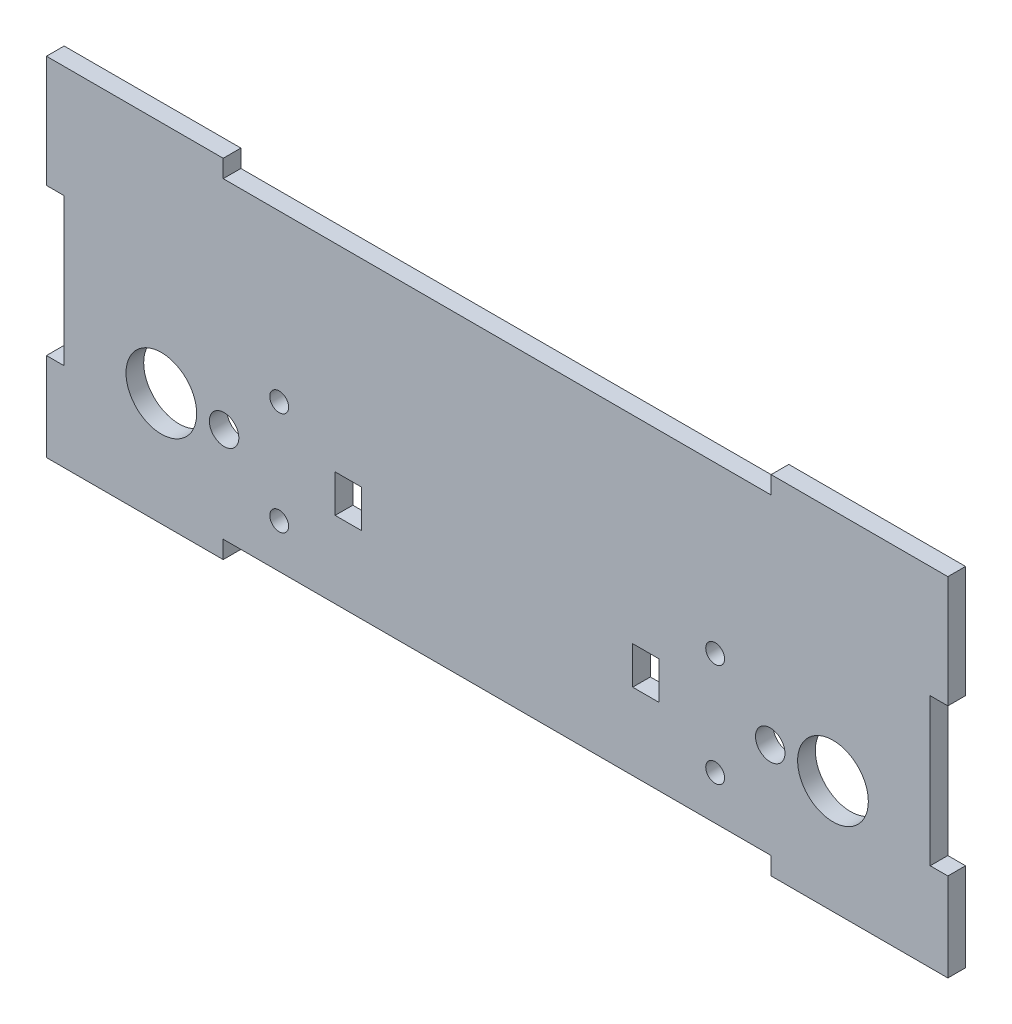
SolidWorks part; units mm, degrees
ref_plane "Plano frontal" through (0, 0, 0) normal (0, 0, 1) x (1, 0, 0)
ref_plane "Plano superior" through (0, 0, 0) normal (0, 1, 0) x (1, 0, 0)
ref_plane "Plano direito" through (0, 0, 0) normal (1, 0, 0) x (0, 0, -1)
sketch "Esboço1" plane through (0, 0, 0) normal (0, 0, 1) x (1, 0, 0)
  line L1 (-76.5, -29.5) -> (76.5, -29.5)
  line L2 (-76.5, -29.5) -> (-76.5, 29.5)
  line L3 (-76.5, 29.5) -> (76.5, 29.5)
  line L4 (76.5, -29.5) -> (76.5, 29.5)
  line L5 (-76.5, -29.5) -> (76.5, 29.5) construction
  line L6 (-76.5, 29.5) -> (76.5, -29.5) construction
  point P0 (0, 0)
  dimension "D1" = 153
  dimension "D2" = 59
extrude "Ressalto-extrusão1" add sketch "Esboço1" along normal blind 3
sketch "Esboço2" plane through (0, 0, 3) normal (0, 0, 1) x (1, 0, 0)
  line L0 (76.5, -29.5) -> (76.5, 29.5) construction
  line L1 (-76.5, 29.5) -> (76.5, 29.5)
  line L2 (-76.5, 29.5) -> (-76.5, 26.5)
  line L3 (-76.5, 26.5) -> (76.5, 26.5)
  line L4 (76.5, 29.5) -> (76.5, 26.5)
  line L5 (-46.5, 29.5) -> (-46.5, 26.5)
  line L6 (46.5, 29.5) -> (46.5, 26.5)
  line L7 (-75.0639, 0) -> (95.5788, 0) construction
  line L8 (46.5, -29.5) -> (46.5, -26.5)
  line L9 (-46.5, -29.5) -> (-46.5, -26.5)
  line L10 (76.5, -29.5) -> (76.5, -26.5)
  line L11 (-76.5, -26.5) -> (76.5, -26.5)
  line L12 (-76.5, -29.5) -> (-76.5, -26.5)
  line L13 (-76.5, -29.5) -> (76.5, -29.5)
  line M8 (-76.5, -29.5) -> (76.5, -29.5)
  dimension "D1" = 3
  dimension "D2" = 30
  dimension "D3" = 30
extrude "Corte-extrusão1" cut sketch "Esboço2" against normal through all contours L6 L1 L5 L3 | L11 L9 L8 M8
sketch "Esboço3" plane through (0, 0, 3) normal (0, 0, 1) x (1, 0, 0)
  line L0 (-76.5, 29.5) -> (-76.5, -29.5) construction
  line L1 (-76.5, 10.5) -> (-73.5, 10.5)
  line L2 (-76.5, 10.5) -> (-76.5, -14.5)
  line L3 (-76.5, -14.5) -> (-73.5, -14.5)
  line L4 (-73.5, 10.5) -> (-73.5, -14.5)
  line L6 (0, -28.8816) -> (0, 36.2557) construction
  line L7 (73.5, 10.5) -> (73.5, -14.5)
  line L8 (76.5, -14.5) -> (73.5, -14.5)
  line L9 (76.5, 10.5) -> (76.5, -14.5)
  line L10 (76.5, 10.5) -> (73.5, 10.5)
  line L11 (-76.5, -29.5) -> (-46.5, -29.5) construction
  dimension "D1" = 3
  dimension "D2" = 25
  dimension "D3" = 15
extrude "Corte-extrusão2" cut sketch "Esboço3" against normal through all
sketch "Esboço4" plane through (0, 0, 0) normal (0, 0, -1) x (-1, 0, 0)
  line L0 (76.5, -14.5) -> (76.5, -29.5) construction
  line L1 (76.5, -29.5) -> (46.5, -29.5) construction
  line L2 (0, 26.9046) -> (0, -42.5067) construction
  circle A0 centre (57, -10.3) radius 6
  circle A1 centre (-57, -10.3) radius 6
  dimension "D1" = 19.5
  dimension "D3" = 12
  dimension "D2" = 19.2
extrude "Corte-extrusão3" cut sketch "Esboço4" against normal through all
sketch "Esboço5" plane through (0, 0, 0) normal (0, 0, 1) x (1, 0, 0)
  line L0 (-73.5, -14.5) -> (-73.5, 10.5) construction
  line L1 (-76.5, -29.5) -> (-46.5, -29.5) construction
  line L2 (0, -37.5398) -> (0, 42.0993) construction
  line L3 (-46.5, -26.5) -> (46.5, -26.5) construction
  line L4 (23, -7.1) -> (27.5, -7.1)
  line L5 (23, -7.1) -> (23, -13.5)
  line L6 (23, -13.5) -> (27.5, -13.5)
  line L7 (27.5, -7.1) -> (27.5, -13.5)
  line L8 (-27.5, -7.1) -> (-27.5, -13.5)
  line L9 (-23, -13.5) -> (-27.5, -13.5)
  line L10 (-23, -7.1) -> (-23, -13.5)
  line L11 (-23, -7.1) -> (-27.5, -7.1)
  circle A0 centre (-37, -1.55) radius 1.6
  circle A1 centre (-37, -19.05) radius 1.6
  circle A2 centre (37, -19.05) radius 1.6
  circle A3 centre (37, -1.55) radius 1.6
  circle A4 centre (-46.35, -10.3) radius 2.5
  circle A5 centre (46.35, -10.3) radius 2.5
  point P24 (23, -10.3)
  dimension "D1" = 3.2
  dimension "D2" = 9.35
  dimension "D5" = 5
  dimension "D3" = 27.95
  dimension "D4" = 10.45
  dimension "D6" = 19.2
  dimension "D7" = 27.15
  dimension "D8" = 4.5
  dimension "D9" = 13
  dimension "D10" = 23
extrude "Corte-extrusão4" cut sketch "Esboço5" along normal through all from surface at 0 starting at face at (-63, -10.3, 0)
